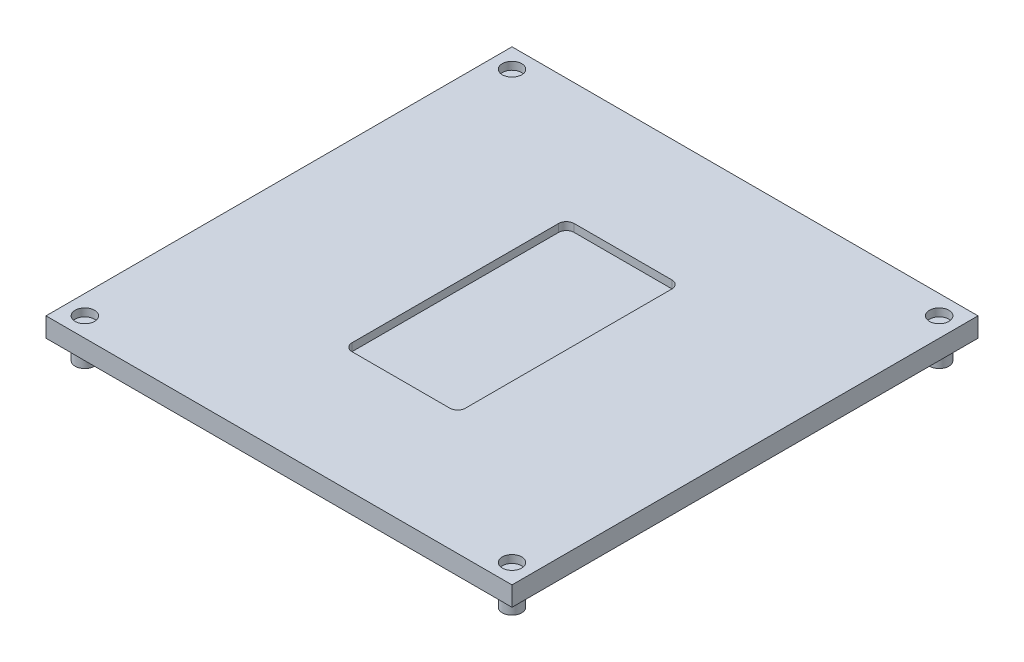
SolidWorks part; units mm, degrees
ref_plane "Front Plane" through (0, 0, 0) normal (0, 0, 1) x (1, 0, 0)
ref_plane "Top Plane" through (0, 0, 0) normal (0, 1, 0) x (1, 0, 0)
ref_plane "Right Plane" through (0, 0, 0) normal (1, 0, 0) x (0, 0, -1)
sketch "Sketch1" plane through (0, 0, 0) normal (0, 1, 0) x (1, 0, 0)
  line L1 (77.4843, 101.0292) -> (-74.9157, 101.0292)
  line L2 (77.4843, 101.0292) -> (77.4843, -51.3708)
  line L3 (77.4843, -51.3708) -> (-74.9157, -51.3708)
  line L4 (-74.9157, 101.0292) -> (-74.9157, -51.3708)
  line L5 (77.4843, 101.0292) -> (-74.9157, -51.3708) construction
  line L6 (77.4843, -51.3708) -> (-74.9157, 101.0292) construction
  point P0 (1.2843, 24.8292)
  dimension "D1" = 152.4
  dimension "D2" = 152.4
extrude "Boss-Extrude1" add sketch "Sketch1" along normal blind 6.35
sketch "Sketch2" plane through (0, 0, 0) normal (0, -1, 0) x (-1, 0, 0)
  line L0 (68.5657, -51.3708) -> (68.5657, 101.0292)
  line L1 (74.9157, -51.3708) -> (-77.4843, -51.3708) construction
  line L2 (-77.4843, 101.0292) -> (74.9157, 101.0292) construction
  line L3 (74.9157, 101.0292) -> (74.9157, -51.3708) construction
  line L5 (-77.4843, -51.3708) -> (-77.4843, 101.0292) construction
  line L6 (-71.1343, -51.3708) -> (-71.1343, 101.0292)
  circle A0 centre (68.5657, -45.0208) radius 3.175
  circle A1 centre (-71.1343, -45.0208) radius 3.175
  circle A2 centre (68.5657, 94.6792) radius 3.175
  circle A3 centre (-71.1343, 94.6792) radius 3.175
  dimension "D4" = 6.35
  dimension "D1" = 6.35
  dimension "D2" = 6.35
  dimension "D3" = 6.35
extrude "Boss-Extrude2" add sketch "Sketch2" along normal blind 6.35 contours L6 A3 | L6 A3 | L0 A2 | L0 A2 | L0 A0 | L0 A0 | L6 A1 | L6 A1
sketch "Sketch3" plane through (0, 6.35, 0) normal (0, 1, 0) x (1, 0, 0)
  line L0 (77.4843, 101.0292) -> (-74.9157, 101.0292) construction
  line L1 (-74.9157, 101.0292) -> (-74.9157, -51.3708) construction
  line L2 (77.4843, -51.3708) -> (77.4843, 101.0292) construction
  line L3 (-74.9157, -51.3708) -> (77.4843, -51.3708) construction
  circle A0 centre (-68.5657, 94.6792) radius 3.175
  circle A1 centre (71.1343, 94.6792) radius 3.175
  circle A2 centre (-68.5657, -45.0208) radius 3.175
  circle A3 centre (71.1343, -45.0208) radius 3.175
  dimension "D1" = 6.35
  dimension "D2" = 6.35
  dimension "D3" = 6.35
  dimension "D4" = 6.35
  dimension "D5" = 6.35
  dimension "D6" = 6.35
  dimension "D7" = 6.35
  dimension "D8" = 6.35
extrude "Cut-Extrude1" cut sketch "Sketch3" against normal blind 2.54
sketch "Sketch4" plane through (0, 6.35, 0) normal (0, 1, 0) x (1, 0, 0)
  line L0 (-74.9157, 24.8292) -> (77.4843, 24.8292)
  line L1 (-74.9157, 101.0292) -> (-74.9157, -51.3708) construction
  line L2 (77.4843, -51.3708) -> (77.4843, 101.0292) construction
  line L3 (1.2843, 101.0292) -> (1.2843, -51.3708)
  line L4 (77.4843, 101.0292) -> (-74.9157, 101.0292) construction
  line L5 (-74.9157, -51.3708) -> (77.4843, -51.3708) construction
  line L7 (-17.2577, 61.1512) -> (19.8263, 61.1512)
  line L8 (-17.2577, 61.1512) -> (-17.2577, -11.4928)
  line L9 (-17.2577, -11.4928) -> (19.8263, -11.4928)
  line L10 (19.8263, 61.1512) -> (19.8263, -11.4928)
  line L11 (-17.2577, 61.1512) -> (19.8263, -11.4928) construction
  line L12 (-17.2577, -11.4928) -> (19.8263, 61.1512) construction
  point P12 (1.2843, 24.8292)
  dimension "D1" = 72.644
  dimension "D2" = 37.084
extrude "Cut-Extrude2" cut sketch "Sketch4" against normal blind 2.54 contours L8 L7 L10 L9
fillet "Fillet1" radius 2.54 1 edges at (-17.2577, 5.08, -61.1512)
fillet "Fillet2" radius 2.54 1 edges at (19.8263, 5.08, -61.1512)
fillet "Fillet3" radius 2.54 1 edges at (-17.2577, 5.08, 11.4928)
fillet "Fillet4" radius 2.54 1 edges at (19.8263, 5.08, 11.4928)
